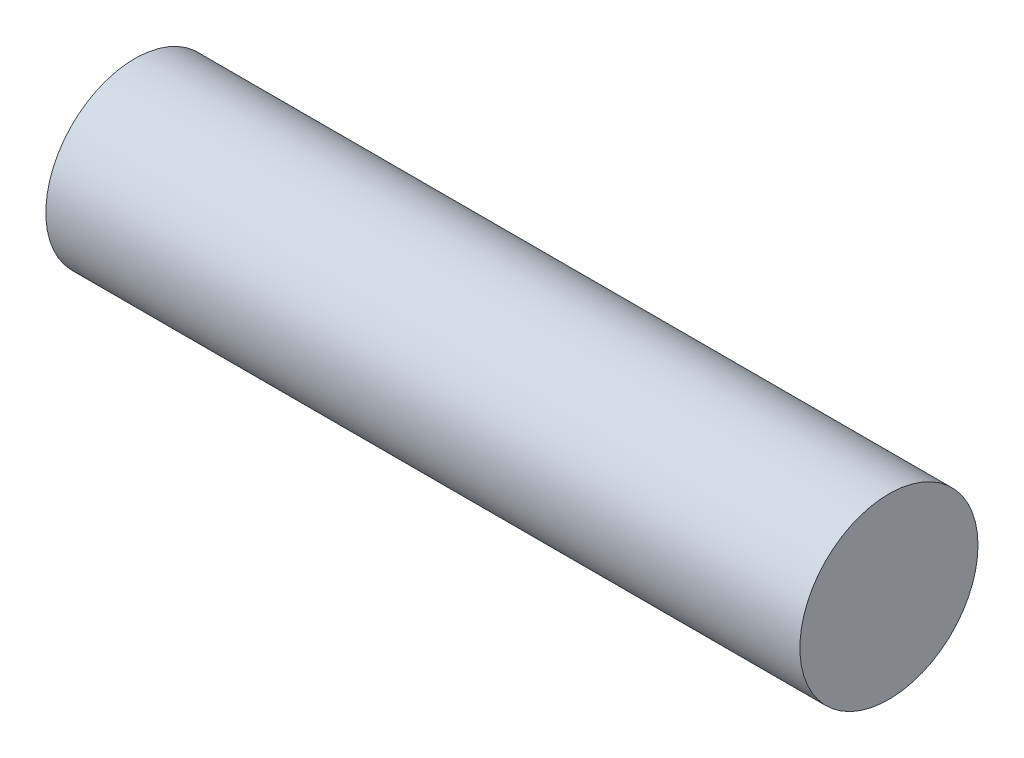
SolidWorks part; units mm, degrees
material "6061 Alloy"
ref_plane "Front Plane" through (0, 0, 0) normal (0, 0, 1) x (1, 0, 0)
ref_plane "Top Plane" through (0, 0, 0) normal (0, 1, 0) x (1, 0, 0)
ref_plane "Right Plane" through (0, 0, 0) normal (1, 0, 0) x (0, 0, -1)
sketch "Sketch2" plane through (0, 0, 0) normal (1, 0, 0) x (0, 0, -1)
  circle A0 centre (0, 0) radius 3
  dimension "D1" = 6
extrude "Boss-Extrude1" add sketch "Sketch2" along normal blind 25.4
